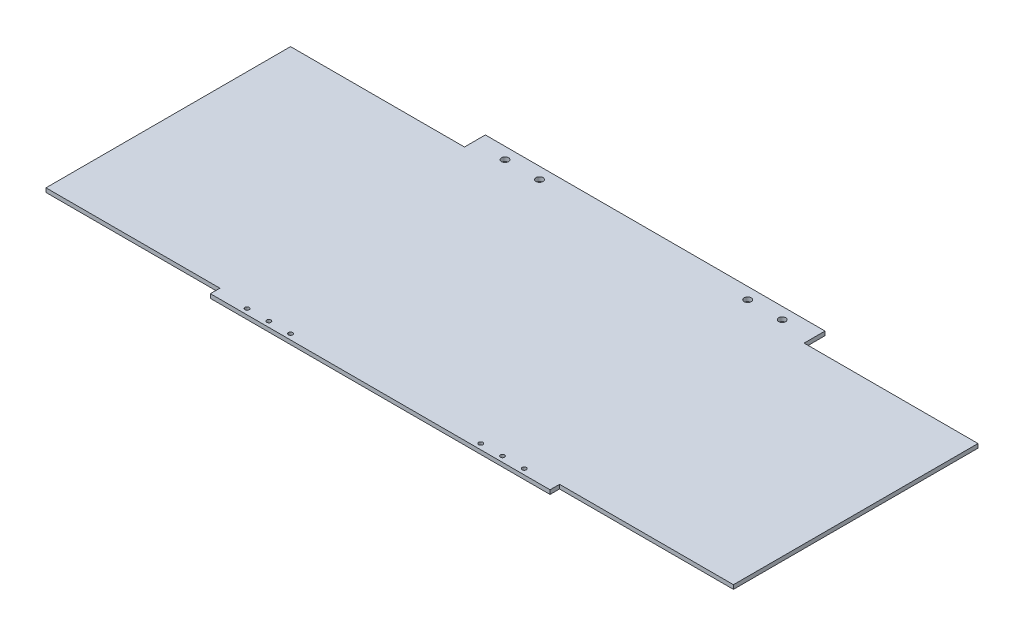
SolidWorks part; units mm, degrees
ref_plane "Front Plane" through (0, 0, 0) normal (0, 0, 1) x (1, 0, 0)
ref_plane "Top Plane" through (0, 0, 0) normal (0, 1, 0) x (1, 0, 0)
ref_plane "Right Plane" through (0, 0, 0) normal (1, 0, 0) x (0, 0, -1)
sketch "Sketch1" plane through (0, 0, 0) normal (0, 1, 0) x (1, 0, 0)
  line L0 (128, 0) -> (128, -7)
  line L1 (0, 0) -> (128, 0)
  line L2 (0, 0) -> (0, 180)
  line L3 (0, 180) -> (128, 180)
  line L4 (506, 0) -> (506, 180)
  line L5 (128, -7) -> (378, -7)
  line L6 (378, -7) -> (378, 0)
  line L7 (0, 90) -> (506, 90) construction
  line L8 (128, 180) -> (128, 195.398)
  line L9 (128, 195.398) -> (378, 195.398)
  line L10 (378, 195.398) -> (378, 180)
  line L11 (253, 195.398) -> (253, -38.1) construction
  line L12 (378, 0) -> (506, 0)
  line L13 (378, 180) -> (506, 180)
  line L14 (128, 186.858) -> (378, 186.858) construction
  line L15 (128, -3) -> (253, -3) construction
  circle A0 centre (151, 186.858) radius 2.564
  circle A1 centre (176.4, 186.858) radius 2.564
  circle A4 centre (151, -3) radius 1.54
  circle A5 centre (183, -3) radius 1.54
  circle A8 centre (329.6, 186.858) radius 2.564
  circle A9 centre (355, 186.858) radius 2.564
  circle A10 centre (167, -3) radius 1.54
  circle A11 centre (323, -3) radius 1.54
  circle A12 centre (339, -3) radius 1.54
  circle A13 centre (355, -3) radius 1.54
  point P10 (253, 90)
  dimension "D7" = 3.08
  dimension "D9" = 5.128
  dimension "D1" = 180
  dimension "D2" = 506
  dimension "D3" = 250
  dimension "D5" = 250
  dimension "D8" = 8.54
  dimension "D10" = 25.4
  dimension "D11" = 23
  dimension "D6" = 6.858
  dimension "D12" = 16
  dimension "D13" = 16
  dimension "D14" = 23
  dimension "D15" = 4
  dimension "D4" = 3
extrude "Boss-Extrude1" add sketch "Sketch1" along normal blind 3
equation "\"cf_tube_outer_diameter\"= 25mm"
equation "\"cf_tube_inner_diameter\" = 21mm"
equation "\"mid_plate_mid_to_top\" = 100mm"
equation "\"mid_plate_mid_to_bottom\" = 30mm"
equation "\"mid_plate_horizontal_spacing\"=250mm"
equation "\"cf_plate_thickness\" =3mm"
equation "\"mid_tube_length\" = 500mm"
equation "\"mid_plate_bottom_width\" = 180mm"
equation "\"D1@Sketch1\"=\"mid_plate_bottom_width\""
equation "\"D2@Sketch1\"=\"mid_tube_length\"+\"cf_plate_thickness\"*2"
equation "\"D1@Boss-Extrude1\"=\"cf_plate_thickness\""
equation "\"D5@Sketch1\"=\"mid_plate_horizontal_spacing\""
equation "\"D3@Sketch1\"=\"mid_plate_horizontal_spacing\""
